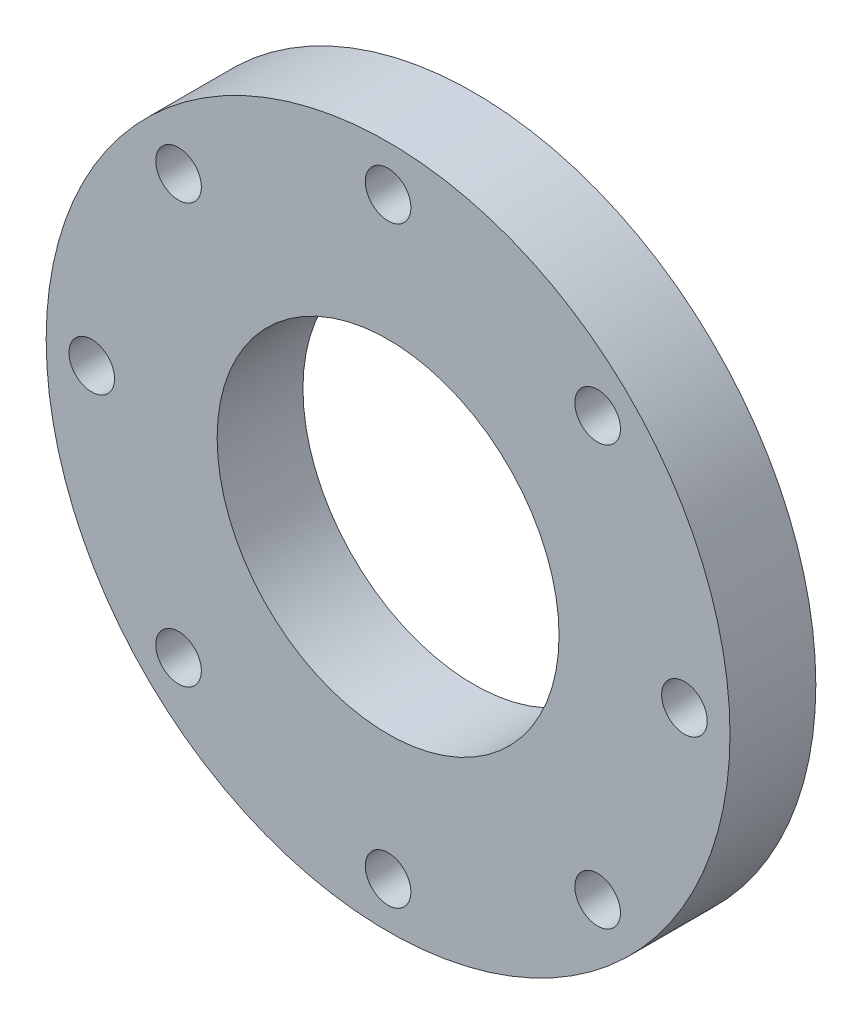
SolidWorks part; units mm, degrees
ref_plane "Front Plane" through (0, 0, 0) normal (0, 0, 1) x (1, 0, 0)
ref_plane "Top Plane" through (0, 0, 0) normal (0, 1, 0) x (1, 0, 0)
ref_plane "Right Plane" through (0, 0, 0) normal (1, 0, 0) x (0, 0, -1)
sketch "Sketch1" plane through (0, 0, 0) normal (0, 0, 1) x (1, 0, 0)
  circle A0 centre (0, 0) radius 15
  circle A1 centre (0, 0) radius 30
  circle A2 centre (0, 0) radius 26 construction
  dimension "D1" = 30
  dimension "D2" = 52
  dimension "D3" = 60
extrude "Boss-Extrude1" add sketch "Sketch1" along normal blind 7.53
hole_wizard "Ø1.0mm Dowel Hole1" positions "Sketch4" profile "Sketch5" hole size "Ø1.0" standard "ISO" end condition through all
sketch "Sketch4" plane through (0, 0, 7.53) normal (0, 0, 1) x (1, 0, 0)
  point P0 (0, 26)
  dimension "D1" = 26
sketch "Sketch5" plane through (0, 26, 7.53) normal (1, 0, 0) x (0, -1, 0)
  line L0 (0, 0) -> (0, 7.53)
  line L1 (0, 7.53) -> (2, 7.53)
  line L2 (2, 7.53) -> (2, 0)
  line L5 (2, 0) -> (0, 0)
  line L11 (0, -6.35) -> (0, 107.95) construction
  dimension "Thru Hole Dia." = 4
  dimension "Thru Hole Depth" = 7.53
pattern_circular "CirPattern1" count 8 over 360 about axis through (0, 0, 0) along (0, 0, 1) of "Ø1.0mm Dowel Hole1"
